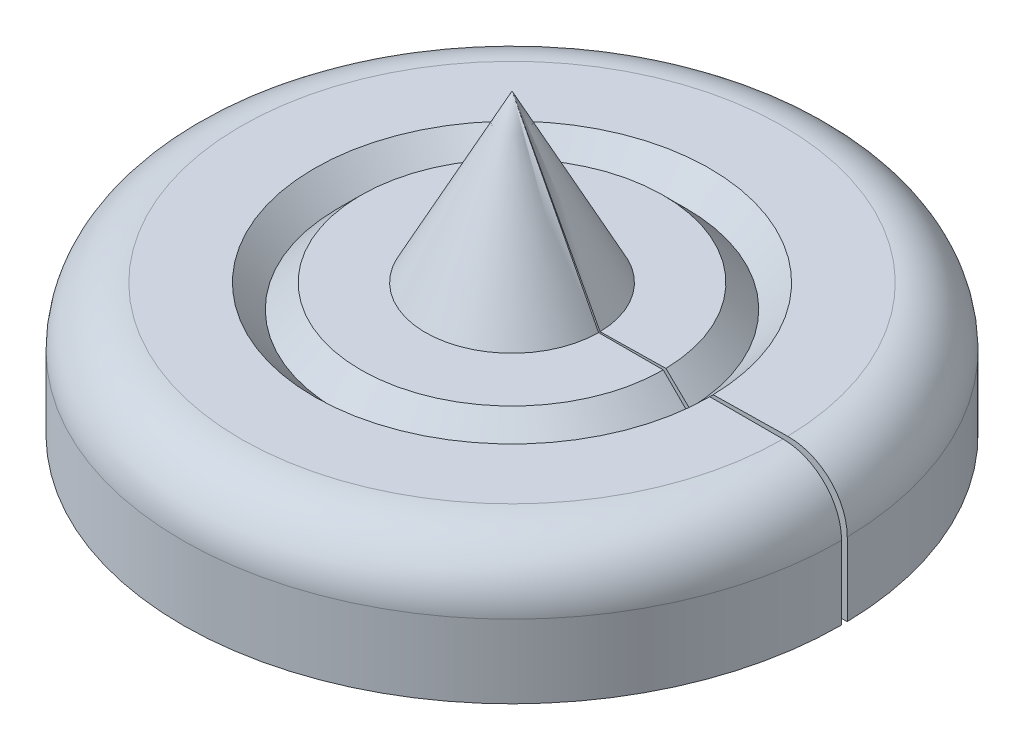
SolidWorks part; units mm, degrees
ref_plane "Front Plane" through (0, 0, 0) normal (0, 0, 1) x (1, 0, 0)
ref_plane "Top Plane" through (0, 0, 0) normal (0, 1, 0) x (1, 0, 0)
ref_plane "Right Plane" through (0, 0, 0) normal (1, 0, 0) x (0, 0, -1)
sketch "Sketch1" plane through (0, 0, 0) normal (0, 0, 1) x (1, 0, 0)
  line L0 (0, 0) -> (25.4, 0) construction
  line L1 (25.4, 0) -> (0, 25.4)
  line L2 (0, 25.4) -> (0, 0) construction
  line L3 (25.4, 0) -> (127, 0)
  line L4 (127, 0) -> (127, 28.2411)
  line L5 (104.4411, 50.8) -> (76.2, 50.8)
  line L6 (76.2, 50.8) -> (67.2464, 41.8464)
  line L7 (67.2464, 41.8464) -> (58.2929, 50.8)
  line L8 (58.2929, 50.8) -> (33.3691, 50.8)
  line L9 (33.3691, 50.8) -> (0, 114.7406)
  line L10 (0, 114.7406) -> (0, 25.4)
  arc A0 (127, 28.2411) -> (104.4411, 50.8) centre (104.4411, 28.2411) ccw
  point P13 (127, 50.8)
  dimension "D5" = 50.8
  dimension "D1" = 25.4
  dimension "D2" = 25.4
  dimension "D3" = 101.6
  dimension "D4" = 50.8
  dimension "D6" = 101.6
  dimension "D7" = 25.4
  dimension "D8" = 25.4
  dimension "D9" = 12.7
revolve "Revolve3" add sketch "Sketch1" angle 359 about L2
